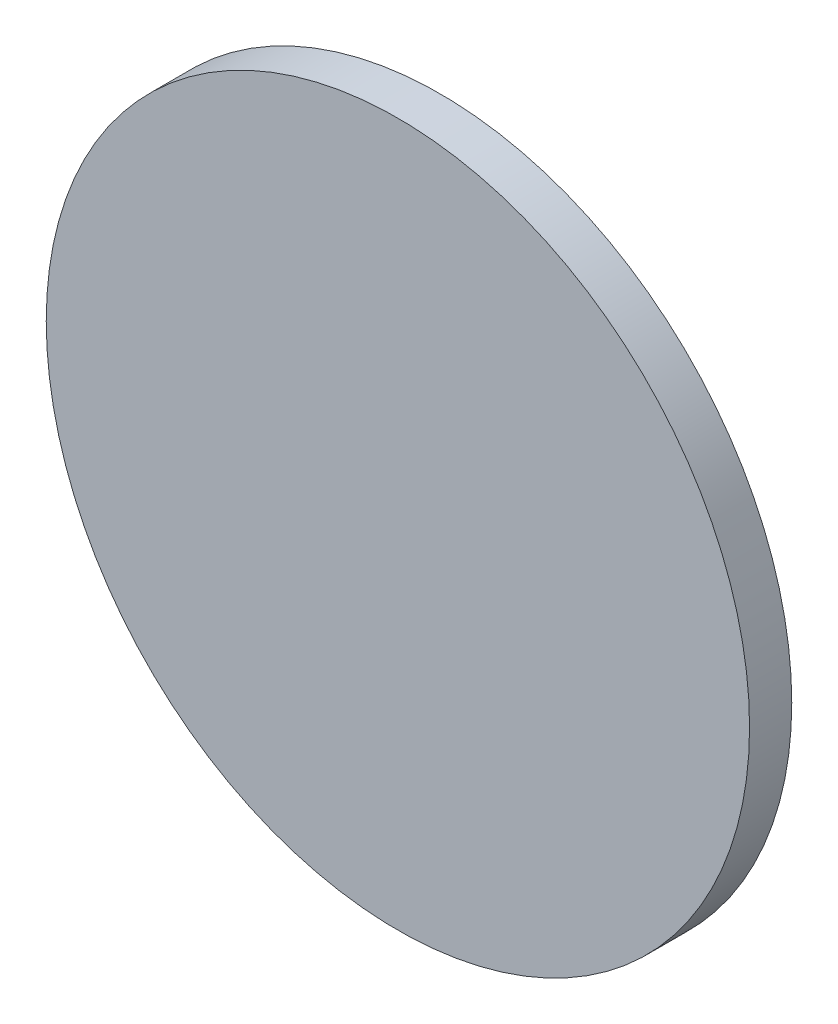
SolidWorks part; units mm, degrees
ref_plane "Přední rovina" through (0, 0, 0) normal (0, 0, 1) x (1, 0, 0)
ref_plane "Horní rovina" through (0, 0, 0) normal (0, 1, 0) x (1, 0, 0)
ref_plane "Pravá rovina" through (0, 0, 0) normal (1, 0, 0) x (0, 0, -1)
sketch "Skica1" plane through (0, 0, 0) normal (0, 0, 1) x (1, 0, 0)
  circle A0 centre (0, 0) radius 5
  dimension "D1" = 10
extrude "Přidat vysunutím1" add sketch "Skica1" along normal blind 0.6
